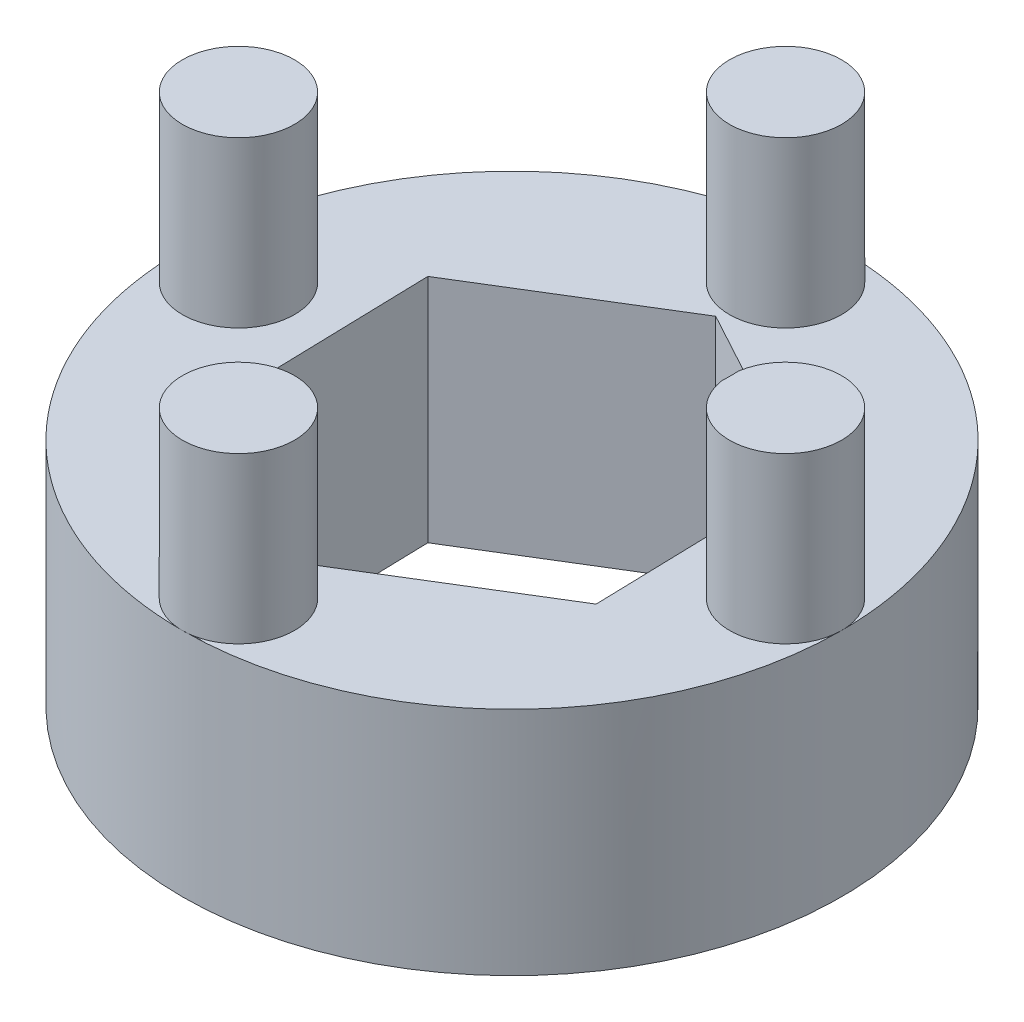
SolidWorks part; units mm, degrees
ref_plane "前视基准面" through (0, 0, 0) normal (0, 0, 1) x (1, 0, 0)
ref_plane "上视基准面" through (0, 0, 0) normal (0, 1, 0) x (1, 0, 0)
ref_plane "右视基准面" through (0, 0, 0) normal (1, 0, 0) x (0, 0, -1)
sketch "草图1" plane through (0, 0, 0) normal (0, 1, 0) x (1, 0, 0)
  circle A0 centre (0, 0) radius 10
extrude "凸台-拉伸1" add sketch "草图1" along normal blind 7
sketch "草图2" plane through (0, 7, 0) normal (0, 1, 0) x (1, 0, 0)
  arc A0 (6.619, -0.2535) -> (6.619, 0.2535) centre (0, 0) ccw
  circle A1 centre (0, 0) radius 10 construction
  circle A2 centre (0, 8.3) radius 1.7
  circle A3 centre (8.3, 0) radius 1.7
  circle A4 centre (0, -8.3) radius 1.7
  circle A5 centre (-8.3, 0) radius 1.7
  point P3 (0, 0)
  point P7 (0, 0)
  point P8 (6.4077, -0.2303)
  point P9 (0, 0)
  point P10 (0, 0)
  point P11 (0, 0)
  point P13 (0, 0)
  point P14 (0, 0)
  point P22 (0, 0)
  point P23 (0, 0)
  dimension "D1" = 8.3
  dimension "D2" = 8.3
  dimension "D3" = 8.3
  dimension "D4" = 8.3
extrude "凸台-拉伸2" add sketch "草图2" along normal blind 5 contours A2 | A5 | A4 | A3 A0
sketch "草图3" plane through (0, 7, 0) normal (0, 1, 0) x (1, 0, 0)
  line L1 (-5.582, 3.029) -> (-5.4142, -3.3196)
  line L2 (-5.4142, -3.3196) -> (0.1678, -6.3486)
  line L3 (0.1678, -6.3486) -> (5.582, -3.029)
  line L4 (5.582, -3.029) -> (5.4142, 3.3196)
  line L5 (5.4142, 3.3196) -> (-0.1678, 6.3486)
  line L6 (-0.1678, 6.3486) -> (-5.582, 3.029)
  circle A0 centre (0, 0) radius 5.5 construction
  dimension "D1" = 5.5
extrude "切除-拉伸1" cut sketch "草图3" against normal blind 7
sketch "草图4" plane through (0, 7, 0) normal (0, 1, 0) x (1, 0, 0)
  circle A0 centre (0.0045, 0.0177) radius 7
  circle A1 centre (0.0045, 0.0177) radius 10
  circle A2 centre (0, 0) radius 10 construction
  point P4 (0, 0)
